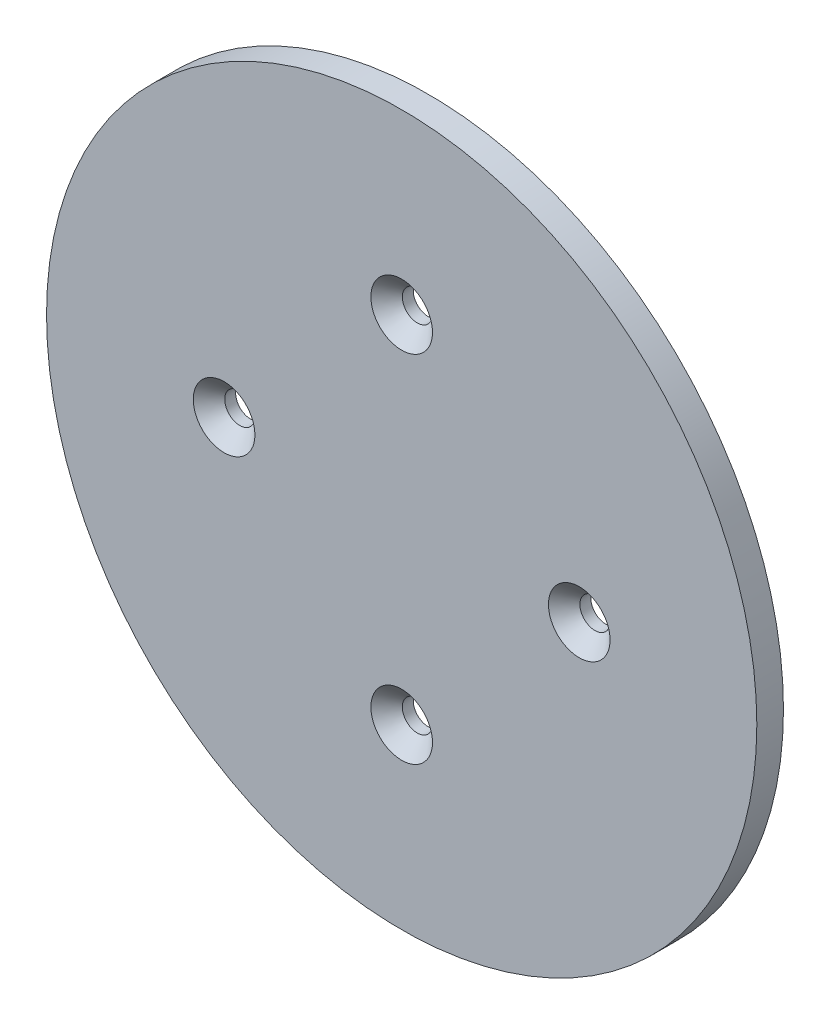
SolidWorks part; units mm, degrees
ref_plane "前视基准面" through (0, 0, 0) normal (0, 0, 1) x (1, 0, 0)
ref_plane "上视基准面" through (0, 0, 0) normal (0, 1, 0) x (1, 0, 0)
ref_plane "右视基准面" through (0, 0, 0) normal (1, 0, 0) x (0, 0, -1)
sketch "草图1" plane through (0, 0, 0) normal (0, 0, 1) x (1, 0, 0)
  circle A0 centre (0, 0) radius 40
  circle A1 centre (0, 0) radius 20 construction
  point P4 (0, 20)
  point P5 (-20, 0)
  point P6 (0, -20)
  point P7 (20, 0)
  dimension "D1" = 40
  dimension "D2" = 80
extrude "凸台-拉伸1" add sketch "草图1" along normal blind 3
hole_wizard "M3 六角凹锥坑头螺钉的锥形沉头孔1" positions "3D草图2" profile "草图3" countersink size "M3" standard "DIN"
sketch3d "3D草图2"
  point P3 (0, 20, 3)
  point P5 (20, 0, 3)
  point P7 (0, -20, 3)
  point P9 (-20, 0, 3)
  point P12 (0, 0, 0)
  point P13 (0, 19.92, 3)
  point P14 (21.6979, -2.3356, 3)
  point P15 (0, 0, 0)
  point P17 (0, 0, 0)
  point P19 (0, 0, 0)
  point P21 (0, 0, 0)
sketch "草图3" plane through (0, 20, 3) normal (1, 0, 0) x (0, -1, 0)
  line L0 (0, 0) -> (0, 11.1415)
  line L1 (0, 11.1415) -> (1.7, 10.12)
  line L2 (1.7, 10.12) -> (1.7, 1.77)
  line L3 (1.7, 1.77) -> (3.47, 0)
  line L5 (3.47, 0) -> (0, 0)
  line L6 (-1.7, 1.77) -> (-3.47, 0) construction
  line L10 (0, 11.1415) -> (-1.7, 10.12) construction
  line L11 (0, -6.35) -> (0, 107.95) construction
  dimension "孔直径" = 3.4
  dimension "孔深度" = 10.12
  dimension "近端锥形沉头孔直径" = 6.94
  dimension "近端锥形沉头孔角度" = 90
  dimension "导头角度" = 118
